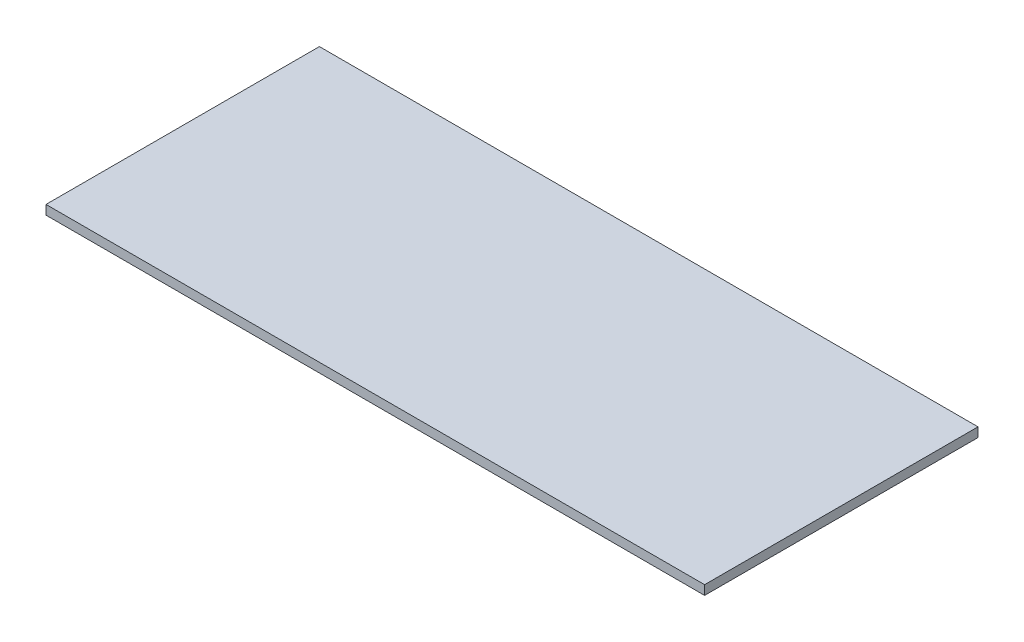
SolidWorks part; units mm, degrees
ref_plane "Front Plane" through (0, 0, 0) normal (0, 0, 1) x (1, 0, 0)
ref_plane "Top Plane" through (0, 0, 0) normal (0, 1, 0) x (1, 0, 0)
ref_plane "Right Plane" through (0, 0, 0) normal (1, 0, 0) x (0, 0, -1)
sketch "Sketch1" plane through (0, 0, 0) normal (0, 1, 0) x (1, 0, 0)
  line L1 (-673.1, -279.4) -> (673.1, -279.4)
  line L2 (-673.1, -279.4) -> (-673.1, 279.4)
  line L3 (-673.1, 279.4) -> (673.1, 279.4)
  line L4 (673.1, -279.4) -> (673.1, 279.4)
  line L5 (-673.1, -279.4) -> (673.1, 279.4) construction
  line L6 (-673.1, 279.4) -> (673.1, -279.4) construction
  point P0 (0, 0)
  dimension "D1" = 1346.2
  dimension "D2" = 558.8
extrude "Boss-Extrude1" add sketch "Sketch1" along normal blind 19.05
